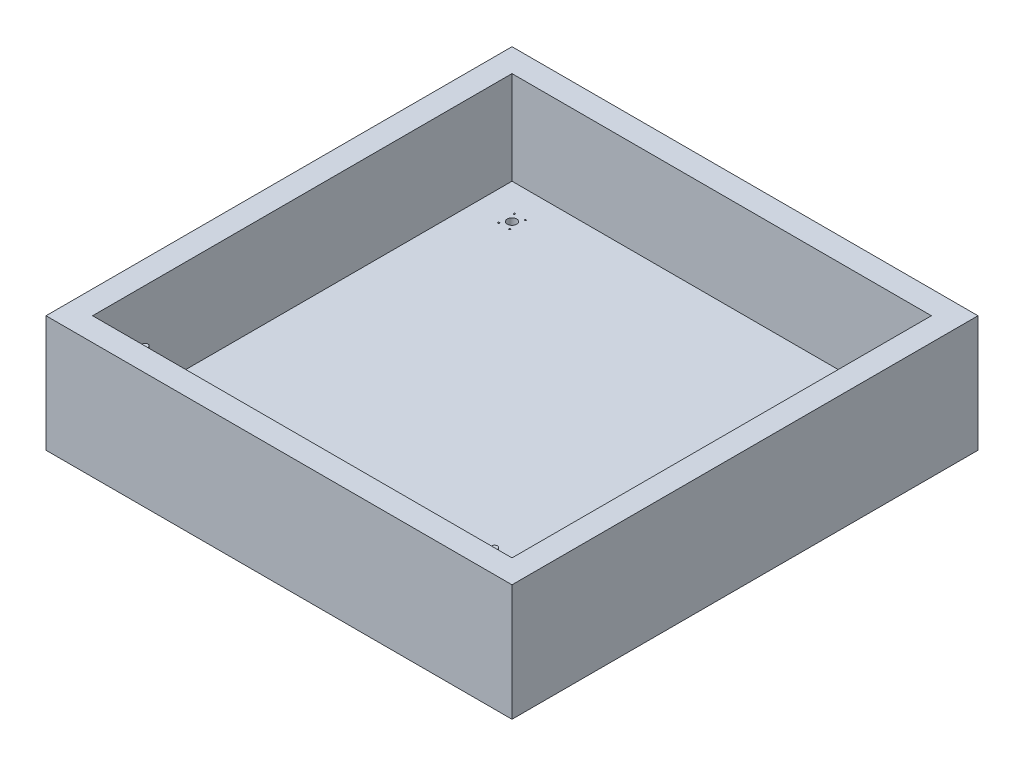
SolidWorks part; units mm, degrees
ref_plane "Front Plane" through (0, 0, 0) normal (0, 0, 1) x (1, 0, 0)
ref_plane "Top Plane" through (0, 0, 0) normal (0, 1, 0) x (1, 0, 0)
ref_plane "Right Plane" through (0, 0, 0) normal (1, 0, 0) x (0, 0, -1)
sketch "Sketch1" plane through (0, 0, 0) normal (0, 1, 0) x (1, 0, 0)
  line L0 (254, 254) -> (-254, 254)
  line L1 (228.6, -228.6) -> (-228.6, -228.6)
  line L2 (228.6, -228.6) -> (228.6, 228.6)
  line L3 (228.6, 228.6) -> (-228.6, 228.6)
  line L4 (-228.6, -228.6) -> (-228.6, 228.6)
  line L5 (228.6, -228.6) -> (-228.6, 228.6) construction
  line L6 (228.6, 228.6) -> (-228.6, -228.6) construction
  line L7 (-254, -254) -> (-254, 254)
  line L8 (254, -254) -> (-254, -254)
  line L9 (254, -254) -> (254, 254)
  point P0 (0, 0)
  dimension "D1" = 457.2
  dimension "D2" = 457.2
  dimension "D3" = 25.4
extrude "Boss-Extrude1" add sketch "Sketch1" along normal blind 101.6
sketch "Sketch2" plane through (0, 0, 0) normal (0, -1, 0) x (1, 0, 0)
  line L1 (254, -254) -> (-254, -254)
  line L2 (254, -254) -> (254, 254)
  line L3 (254, 254) -> (-254, 254)
  line L4 (-254, -254) -> (-254, 254)
  line L5 (254, -254) -> (-254, 254) construction
  line L6 (254, 254) -> (-254, -254) construction
  point P0 (0, 0)
extrude "Boss-Extrude2" add sketch "Sketch2" along normal blind 25.4
sketch "Sketch3" plane through (0, 0, 0) normal (0, 1, 0) x (1, 0, 0)
  line L0 (-196.596, 200.65) -> (-184.404, 200.65)
  line L1 (-198.12, 199.126) -> (-198.12, 181.874)
  line L2 (-196.596, 180.35) -> (-184.404, 180.35)
  line L3 (-182.88, 199.126) -> (-182.88, 181.874)
  line L4 (-228.6, 228.6) -> (-228.6, -228.6) construction
  line L5 (228.6, 228.6) -> (-228.6, 228.6) construction
  line L6 (0, 0) -> (94.6489, 0) construction
  line L7 (0, 0) -> (0, 126.8099) construction
  line L8 (182.88, 199.126) -> (182.88, 181.874)
  line L9 (196.596, 180.35) -> (184.404, 180.35)
  line L10 (198.12, 199.126) -> (198.12, 181.874)
  line L11 (196.596, 200.65) -> (184.404, 200.65)
  line L12 (-228.6, -228.6) -> (228.6, -228.6) construction
  arc A0 (-196.596, 200.65) -> (-198.12, 199.126) centre (-196.596, 199.126) ccw
  arc A1 (-198.12, 181.874) -> (-196.596, 180.35) centre (-196.596, 181.874) ccw
  arc A2 (-184.404, 180.35) -> (-182.88, 181.874) centre (-184.404, 181.874) ccw
  arc A3 (-184.404, 200.65) -> (-182.88, 199.126) centre (-184.404, 199.126) cw
  circle A4 centre (-184.596, 182.126) radius 0.8
  circle A5 centre (-184.596, 199.126) radius 0.8
  circle A6 centre (-196.596, 199.126) radius 0.8
  circle A7 centre (-196.596, 182.126) radius 0.8
  circle A8 centre (-190.5, 190.5) radius 5.08
  circle A9 centre (190.5, 190.5) radius 5.08
  circle A10 centre (196.596, 182.126) radius 0.8
  circle A11 centre (196.596, 199.126) radius 0.8
  circle A12 centre (184.596, 199.126) radius 0.8
  circle A13 centre (184.596, 182.126) radius 0.8
  arc A14 (184.404, 200.65) -> (182.88, 199.126) centre (184.404, 199.126) ccw
  arc A15 (184.404, 180.35) -> (182.88, 181.874) centre (184.404, 181.874) cw
  arc A16 (198.12, 181.874) -> (196.596, 180.35) centre (196.596, 181.874) cw
  arc A17 (196.596, 200.65) -> (198.12, 199.126) centre (196.596, 199.126) cw
  circle A28 centre (-190.5, -209.55) radius 3.175
  circle A29 centre (190.5, -209.55) radius 3.175
  point P50 (-190.5, -206.8543)
  point P55 (190.5, -209.55)
  dimension "D10" = 6.35
  dimension "D1" = 10.15
  dimension "D2" = 1.524
  dimension "D3" = 7.62
  dimension "D4" = 12.192
  dimension "D5" = 17.252
  dimension "D6" = 38.1
  dimension "D7" = 38.1
  dimension "D8" = 12
  dimension "D9" = 17
  dimension "D11" = 19.05
extrude "Cut-Extrude1" cut sketch "Sketch3" against normal blind 29.21 contours A6 | A5 | A8 | A4 | A7 | A28 | A29
sketch "Sketch4" plane through (0, 0, 0) normal (0, 1, 0) x (1, 0, 0)
  circle A0 centre (190.5, -209.55) radius 3.175
  dimension "D1" = 6.35
extrude "Boss-Extrude3" add sketch "Sketch4" along normal blind 82.804 separate body
sketch "Sketch5" plane through (0, 0, 0) normal (0, 1, 0) x (1, 0, 0)
  circle A0 centre (-190.5, -209.55) radius 3.175
extrude "Boss-Extrude4" add sketch "Sketch5" along normal blind 82.804 separate body
